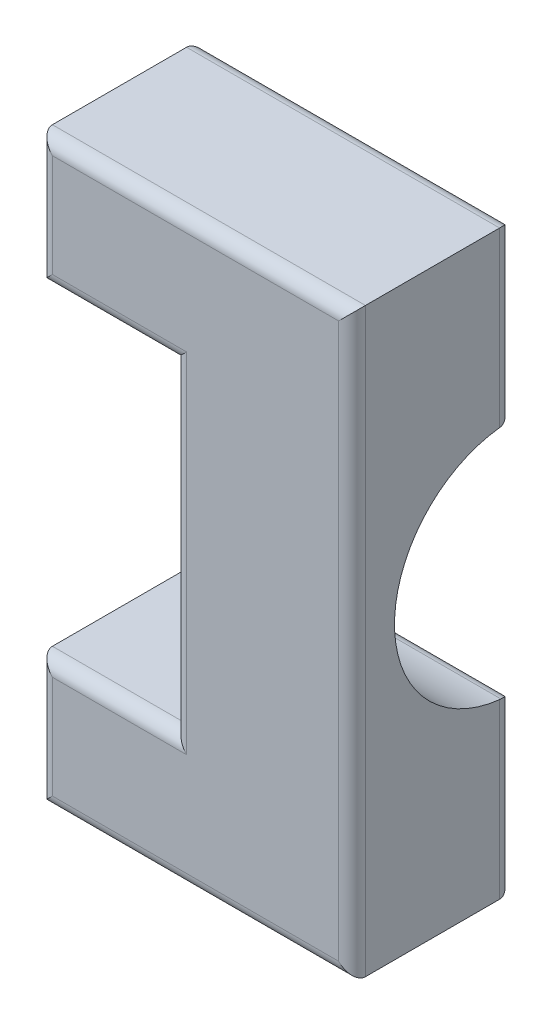
SolidWorks part; units mm, degrees
material "ABS"
ref_plane "正面" through (0, 0, 0) normal (0, 0, 1) x (1, 0, 0)
ref_plane "平面" through (0, 0, 0) normal (0, 1, 0) x (1, 0, 0)
ref_plane "右側面" through (0, 0, 0) normal (1, 0, 0) x (0, 0, -1)
sketch "ｽｹｯﾁ1" plane through (0, 0, 0) normal (0, 0, 1) x (1, 0, 0)
  line L0 (0, 0) -> (0, 14.5)
  line L5 (0, 65) -> (35, 65)
  line L11 (35, 0) -> (0, 0)
  line L12 (0, 50.5) -> (15, 50.5)
  line L13 (35, 32.5) -> (95, 32.5) construction
  line L14 (15, 14.5) -> (0, 14.5)
  line L16 (35, 65) -> (35, 0)
  line L17 (0, 50.5) -> (0, 65)
  line L18 (15, 14.5) -> (15, 50.5)
  point P2 (35, 32.5)
  dimension "D2" = 18
  dimension "D1" = 65
  dimension "D3" = 15
  dimension "D4" = 18
  dimension "D7" = 35
extrude "ﾎﾞｽ - 押し出し1" add sketch "ｽｹｯﾁ1" along normal blind 18
sketch "ｽｹｯﾁ2" plane through (0, 0, 0) normal (-1, 0, 0) x (0, 0, 1)
  line L0 (0, 65) -> (0, 0) construction
  circle A0 centre (0, 32.5) radius 13.25
  point P2 (0, 0)
  point P3 (0, 0)
  point P7 (0, 65)
  dimension "D1" = 26.5
extrude "ｶｯﾄ - 押し出し1" cut sketch "ｽｹｯﾁ2" against normal through all
fillet "ﾌｨﾚｯﾄ1" radius 1.5 21 edges at (17.5, 65, 0) (0, 7.25, 0) (7.5, 50.5, 0) (15, 48.125, 0) (25, 19.25, 0) (25, 45.75, 0) (7.5, 14.5, 0) (17.5, 0, 0) (35, 9.625, 0) (15, 16.875, 0) (35, 32.5, 18) (17.5, 0, 18) (0, 7.25, 18) (7.5, 14.5, 18) (15, 32.5, 18) (7.5, 50.5, 18) (17.5, 65, 18) (15, 32.5, 13.25) (0, 57.75, 0) (35, 55.375, 0) (0, 57.75, 18)
